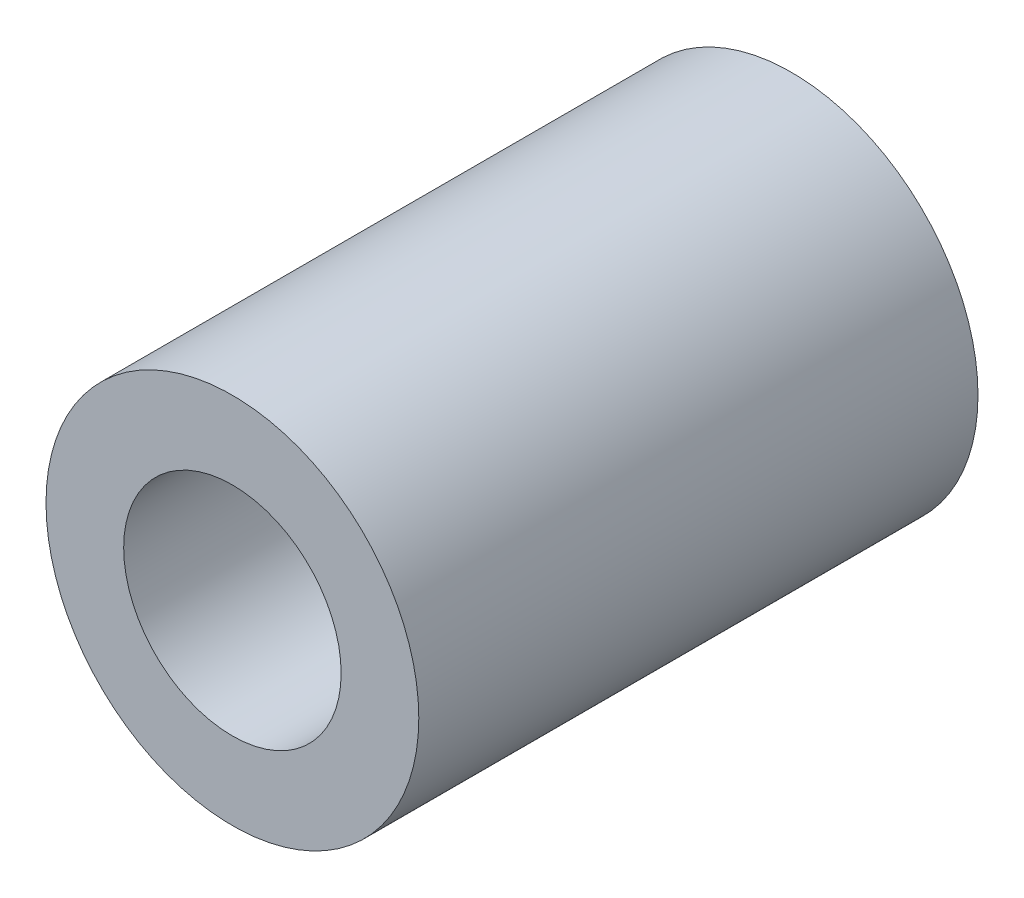
SolidWorks part; units mm, degrees
ref_plane "Front Plane" through (0, 0, 0) normal (0, 0, 1) x (1, 0, 0)
ref_plane "Top Plane" through (0, 0, 0) normal (0, 1, 0) x (1, 0, 0)
ref_plane "Right Plane" through (0, 0, 0) normal (1, 0, 0) x (0, 0, -1)
ref_plane "Plane1" through (0, 0.8065, 0) normal (0, 1, 0) x (1, 0, 0)
sketch "Sketch1" plane through (0, 0.8065, 0) normal (0, 1, 0) x (1, 0, 0)
  line L0 (3.1378, -10) -> (3.1378, -4)
  line L1 (3.1378, -4) -> (2.3045, -4)
  line L2 (2.3045, -4) -> (2.3045, -10)
  line L3 (2.3045, -10) -> (3.1378, -10)
  line L4 (1.1378, 0) -> (1.1378, -10) construction
  dimension "D1" = 6
revolve "Revolve1" add sketch "Sketch1" angle 360 about L4
